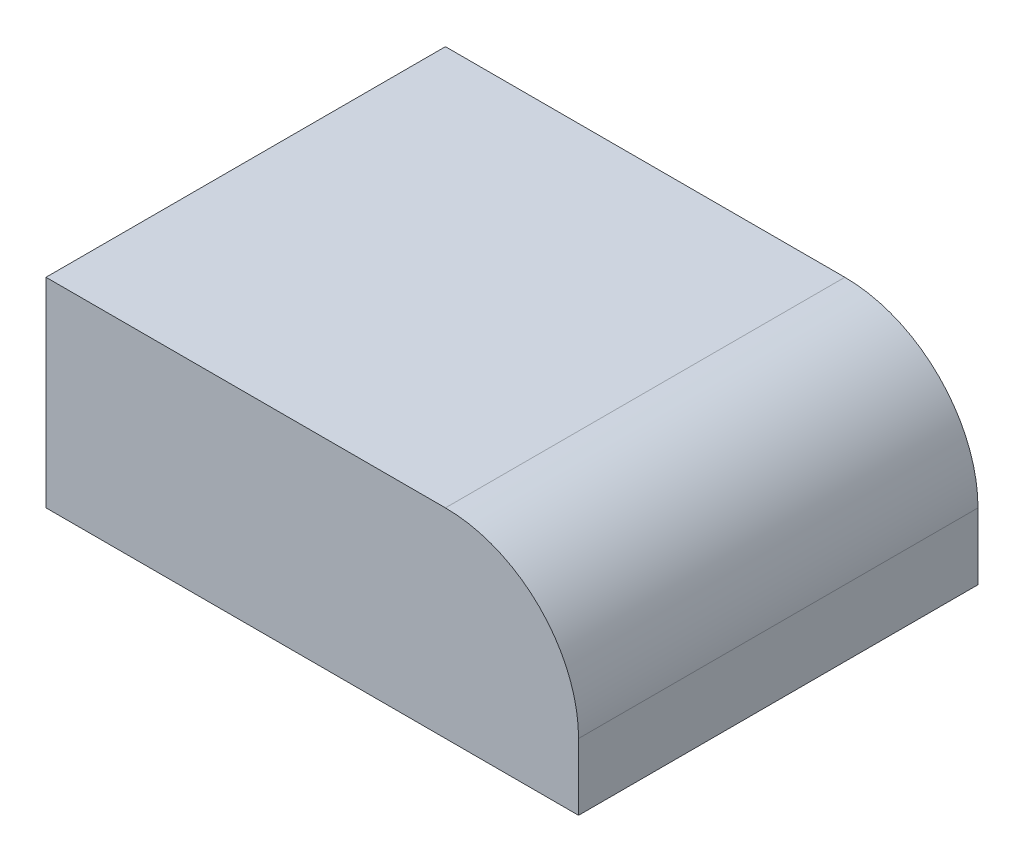
SolidWorks part; units mm, degrees
ref_plane "Front Plane" through (0, 0, 0) normal (0, 0, 1) x (1, 0, 0)
ref_plane "Top Plane" through (0, 0, 0) normal (0, 1, 0) x (1, 0, 0)
ref_plane "Right Plane" through (0, 0, 0) normal (1, 0, 0) x (0, 0, -1)
sketch "Sketch1" plane through (0, 0, 0) normal (0, 0, 1) x (1, 0, 0)
  line L1 (0, 0) -> (50.8, 0)
  line L2 (0, 0) -> (0, 19.05)
  line L3 (0, 19.05) -> (50.8, 19.05)
  line L4 (50.8, 0) -> (50.8, 19.05)
  dimension "D1" = 19.05
  dimension "D2" = 50.8
extrude "Boss-Extrude1" add sketch "Sketch1" along normal blind 38.1
fillet "Fillet1" radius 12.7 1 edges at (50.8, 19.05, 19.05)
